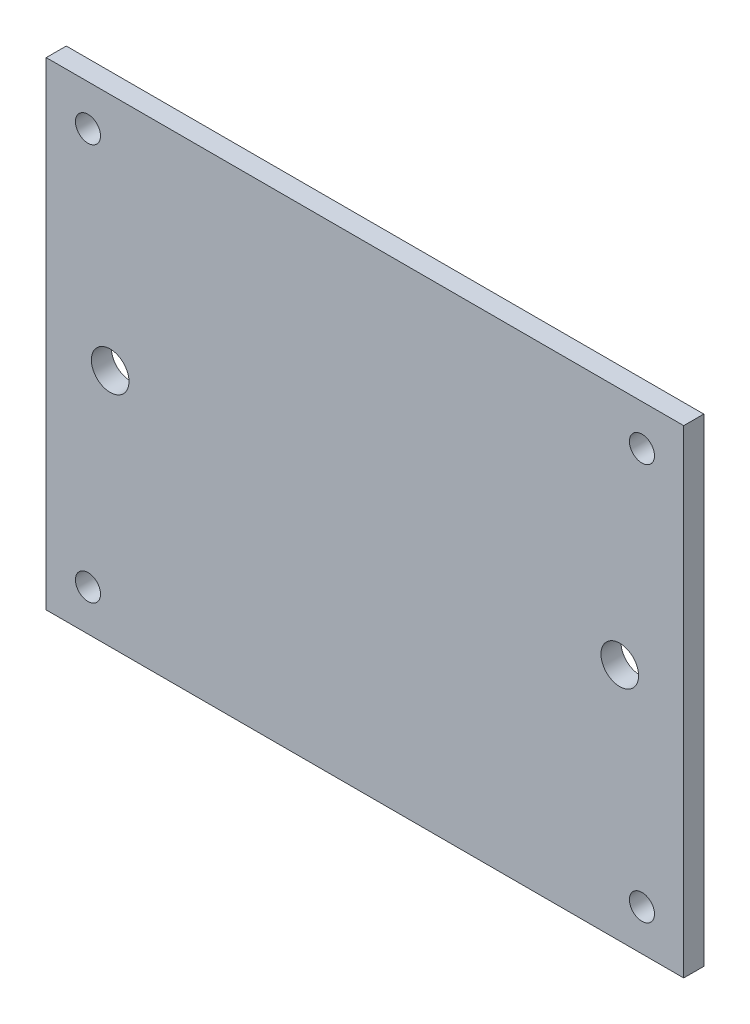
SolidWorks part; units mm, degrees
ref_plane "Front Plane" through (0, 0, 0) normal (0, 0, 1) x (1, 0, 0)
ref_plane "Top Plane" through (0, 0, 0) normal (0, 1, 0) x (1, 0, 0)
ref_plane "Right Plane" through (0, 0, 0) normal (1, 0, 0) x (0, 0, -1)
sketch "Sketch1" plane through (0, 0, 0) normal (0, 0, 1) x (1, 0, 0)
  line L0 (0, -40.427) -> (0, 40.427) construction
  line L1 (-25.42, -19.075) -> (25.42, -19.075)
  line L2 (-25.42, -19.075) -> (-25.42, 19.075)
  line L3 (-25.42, 19.075) -> (25.42, 19.075)
  line L4 (25.42, -19.075) -> (25.42, 19.075)
  line L7 (-52.9839, 0) -> (52.9839, 0) construction
  circle A2 centre (-22.09, 15.825) radius 1
  circle A3 centre (22.09, 15.825) radius 1
  circle A4 centre (22.09, -15.825) radius 1
  circle A5 centre (-22.09, -15.825) radius 1
  circle A6 centre (-20.32, 0) radius 1.5
  circle A7 centre (20.32, 0) radius 1.5
  point P0 (0, 0)
  point P9 (0, 0)
  point P14 (0, 0)
  dimension "D3" = 3.33
  dimension "D4" = 25.42
  dimension "D5" = 2
  dimension "D7" = 3
  dimension "D8" = 5.1
  dimension "D1" = 50.84
  dimension "D2" = 38.15
  dimension "D6" = 3.25
  dimension "D9" = 19.075
extrude "Boss-Extrude1" add sketch "Sketch1" along normal blind 1.6
